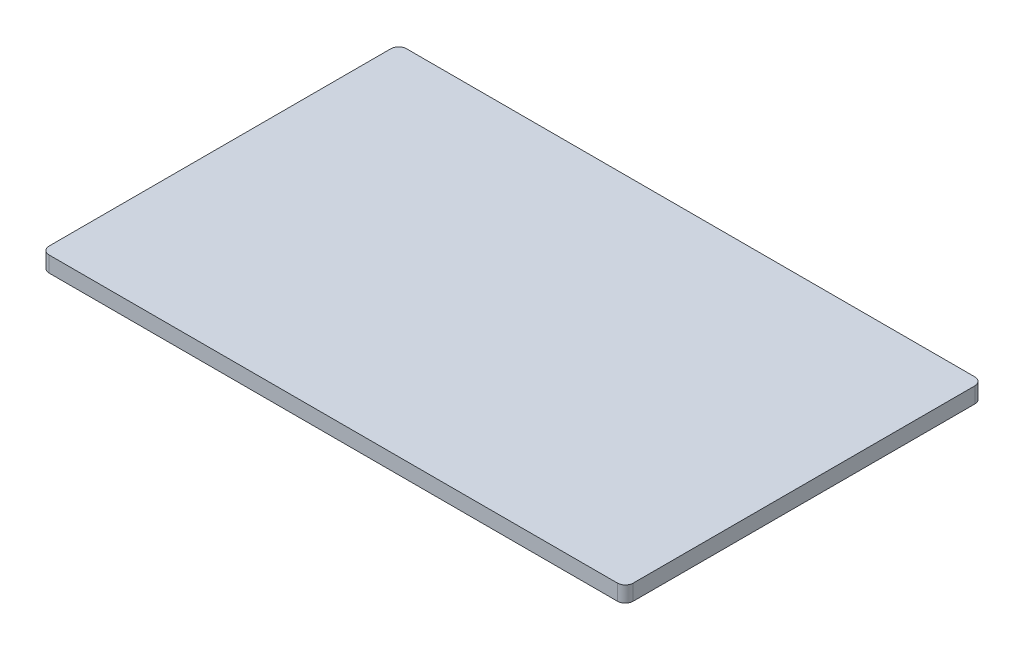
SolidWorks part; units mm, degrees
material "Akryl (Średnie-wysokie uderzenie)"
ref_plane "Płaszczyzna przednia" through (0, 0, 0) normal (0, 0, 1) x (1, 0, 0)
ref_plane "Płaszczyzna górna" through (0, 0, 0) normal (0, 1, 0) x (1, 0, 0)
ref_plane "Płaszczyzna prawa" through (0, 0, 0) normal (1, 0, 0) x (0, 0, -1)
sketch "Szkic1" plane through (0, 0, 0) normal (0, 1, 0) x (1, 0, 0)
  line L0 (-64.7989, -4.0459) -> (9.8011, -4.0459) construction
  line L1 (9.8011, -4.0459) -> (9.8011, 41.7541) construction
  line L2 (9.8011, 41.7541) -> (-64.7989, 41.7541) construction
  line L3 (-64.7989, 41.7541) -> (-64.7989, -4.0459) construction
  line L4 (-64.5989, -3.8459) -> (9.6011, -3.8459)
  line L5 (9.6011, -3.8459) -> (9.6011, 41.5541)
  line L6 (9.6011, 41.5541) -> (-64.5989, 41.5541)
  line L7 (-64.5989, 41.5541) -> (-64.5989, -3.8459)
  dimension "D1" = 0.2
extrude "Dodanie-wyciągnięcie1" add sketch "Szkic1" along normal blind 2
fillet "Zaokrąglenie1" radius 1 4 edges at (-64.5989, 1, -41.5541) (9.6011, 1, -41.5541) (9.6011, 1, 3.8459) (-64.5989, 1, 3.8459)
